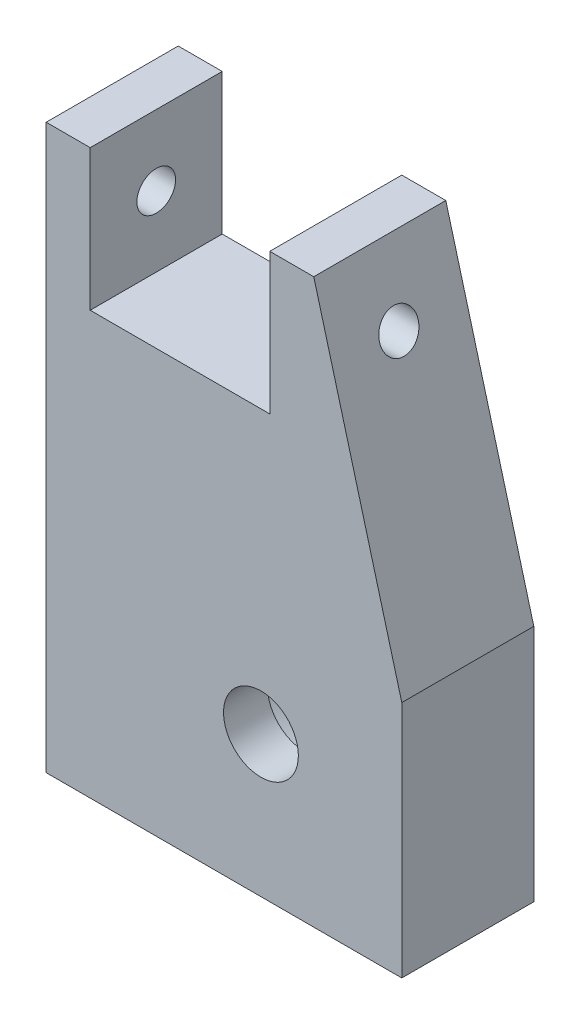
SolidWorks part; units mm, degrees
material "ABS"
ref_plane "Płaszczyzna przednia" through (0, 0, 0) normal (0, 0, 1) x (1, 0, 0)
ref_plane "Płaszczyzna górna" through (0, 0, 0) normal (0, 1, 0) x (1, 0, 0)
ref_plane "Płaszczyzna prawa" through (0, 0, 0) normal (1, 0, 0) x (0, 0, -1)
sketch "Szkic1" plane through (0, 0, 0) normal (0, 0, 1) x (1, 0, 0)
  line L0 (-10.2, 8) -> (-15.2, 8)
  line L1 (-10.2, -8) -> (10.2, -8)
  line L2 (-10.2, -8) -> (-10.2, 8)
  line L3 (-10.2, 8) -> (10.2, 8)
  line L4 (10.2, -8) -> (10.2, 8)
  line L5 (-10.2, -8) -> (10.2, 8) construction
  line L6 (-10.2, 8) -> (10.2, -8) construction
  line L7 (-15.2, 8) -> (-15.2, -56)
  line L8 (-15.2, -56) -> (25.2, -56)
  line L9 (25.2, -56) -> (25.2, -28.9)
  line L10 (15.2, 8) -> (10.2, 8)
  line L11 (25.2, -28.9) -> (15.2, 8)
  circle A0 centre (9.2, -40) radius 4
  circle A1 centre (9.2, -40) radius 11.1
  point P0 (0, 0)
  point P13 (36.0241, -28.9)
  point P14 (8.0497, -40)
  dimension "D5" = 8
  dimension "D8" = 16
  dimension "D1" = 5
  dimension "D2" = 20.4
  dimension "D3" = 16
  dimension "D4" = 5
  dimension "D6" = 32
  dimension "D7" = 1
  dimension "D9" = 27.1
  dimension "D10" = 16
extrude "Dodanie-wyciągnięcie1" add sketch "Szkic1" along normal blind 15 contours L9 L11 L10 L4 L1 L2 L0 L7 L8 A1
sketch "Szkic2" plane through (0, 0, 15) normal (0, 0, 1) x (1, 0, 0)
  line L9 (25.2, -56) -> (25.2, -28.9)
  line L10 (25.2, -28.9) -> (15.2, 8)
  line L11 (15.2, 8) -> (10.2, 8)
  line L12 (10.2, 8) -> (10.2, -8)
  line L13 (10.2, -8) -> (-10.2, -8)
  line L14 (-10.2, -8) -> (-10.2, 8)
  line L15 (-10.2, 8) -> (-15.2, 8)
  line L16 (-15.2, 8) -> (-15.2, -56)
  line L17 (-15.2, -56) -> (25.2, -56)
  line L18 (25.2, -56) -> (25.2, -28.9)
  line L19 (25.2, -28.9) -> (15.2, 8)
  line L20 (15.2, 8) -> (10.2, 8)
  line L21 (10.2, 8) -> (10.2, -8)
  line L22 (10.2, -8) -> (-10.2, -8)
  line L23 (-10.2, -8) -> (-10.2, 8)
  line L24 (-10.2, 8) -> (-15.2, 8)
  line L25 (-15.2, 8) -> (-15.2, -56)
  line L26 (-15.2, -56) -> (25.2, -56)
  circle A0 centre (9.2, -40) radius 11.1 construction
  circle A1 centre (9.2, -40) radius 11.1
  circle A2 centre (9.2, -40) radius 4.25
  circle M11 centre (9.2, -40) radius 11.1
  dimension "D2" = 8.5
  dimension "D1" = 0
extrude "Dodanie-wyciągnięcie2" add sketch "Szkic2" against normal blind 5 contours A2 M11
sketch "Szkic3" plane through (-15.2, 0, 0) normal (-1, 0, 0) x (0, 0, 1)
  line L0 (15, -8) -> (0, -8) construction
  line L1 (15, -8) -> (0, -8)
  line L2 (15, 8) -> (15, -56) construction
  circle A0 centre (7.5, 0) radius 2.2
  point P4 (0, 0)
  dimension "D1" = 4.4
  dimension "D2" = 8
  dimension "D3" = 7.5
extrude "Wytnij-wyciągnięcie1" cut sketch "Szkic3" against normal through all contours A0
